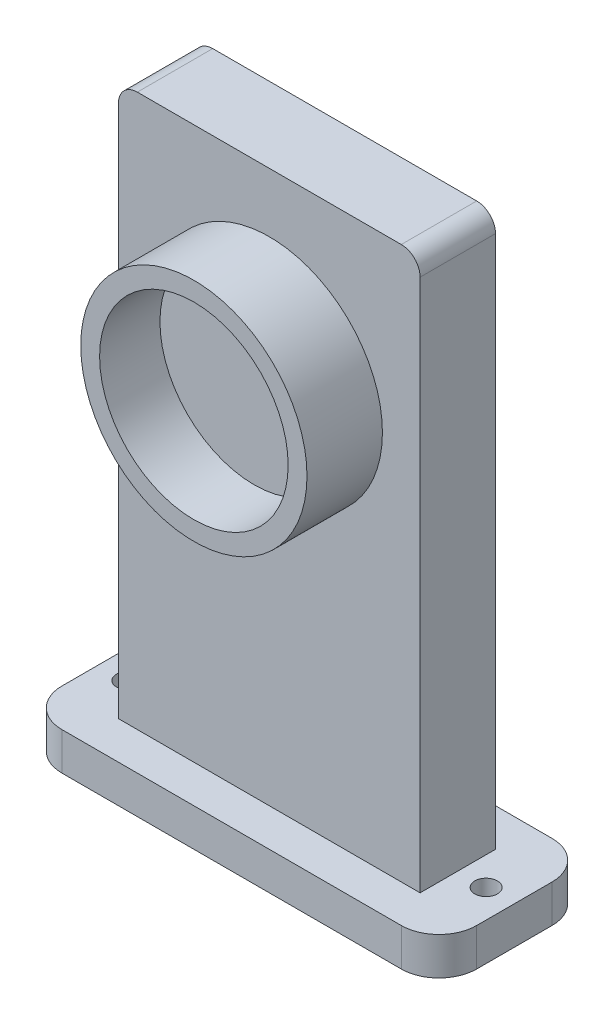
SolidWorks part; units mm, degrees
ref_plane "Front Plane" through (0, 0, 0) normal (0, 0, 1) x (1, 0, 0)
ref_plane "Top Plane" through (0, 0, 0) normal (0, 1, 0) x (1, 0, 0)
ref_plane "Right Plane" through (0, 0, 0) normal (1, 0, 0) x (0, 0, -1)
sketch "Sketch1" plane through (0, 0, 0) normal (0, 0, 1) x (1, 0, 0)
  line L5 (-20, 55.35) -> (20, -55.35) construction
  line L6 (-20, -55.35) -> (20, 55.35) construction
  line L14 (-20, 55.35) -> (20, 55.35)
  line L15 (-20, 55.35) -> (-20, -55.35)
  line L16 (-20, -55.35) -> (20, -55.35)
  line L17 (20, 55.35) -> (20, -55.35)
  point P0 (0, 0)
  dimension "D1" = 110.7
  dimension "D2" = 40
extrude "Boss-Extrude1" add sketch "Sketch1" along normal blind 10
sketch "Sketch4" plane through (0, 0, 10) normal (0, 0, 1) x (1, 0, 0)
  circle A0 centre (0, 0) radius 15
  dimension "D1" = 30
extrude "Boss-Extrude3" add sketch "Sketch4" along normal blind 10
sketch "Sketch5" plane through (0, 0, 20) normal (0, 0, 1) x (1, 0, 0)
  circle A0 centre (0, 0) radius 12.5
  dimension "D1" = 25
extrude "Cut-Extrude2" cut sketch "Sketch5" against normal blind 8
sketch "Sketch6" plane through (0, 55.35, 0) normal (0, 1, 0) x (1, 0, 0)
  line L1 (-20, 0) -> (20, 0)
  line L2 (-20, 0) -> (-20, -10)
  line L3 (-20, -10) -> (20, -10)
  line L4 (20, 0) -> (20, -10)
extrude "Cut-Extrude3" cut sketch "Sketch6" against normal blind 32.5
fillet "Fillet4" radius 2.5 2 edges at (20, 22.85, 5) (-20, 22.85, 5)
sketch "Sketch11" plane through (0, -55.35, 0) normal (0, -1, 0) x (1, 0, 0)
  line L0 (0, 10) -> (0, 0) construction
  line L1 (-20, 10) -> (20, 10) construction
  line L2 (-27.5, 5) -> (-20, 5) construction
  line L3 (-22.5, 15) -> (22.5, 15)
  line L4 (-27.5, 10) -> (-27.5, 0)
  line L5 (-22.5, -5) -> (22.5, -5)
  line L6 (27.5, 10) -> (27.5, 0)
  line L7 (-27.5, 15) -> (27.5, -5) construction
  line L8 (-27.5, -5) -> (27.5, 15) construction
  line L9 (-20, 10) -> (-20, 0) construction
  line L11 (-20, 10) -> (20, 10)
  line L12 (-20, 10) -> (-20, 0)
  line L13 (-20, 0) -> (20, 0)
  line L14 (20, 10) -> (20, 0)
  line L15 (-20, 10) -> (20, 0) construction
  line L16 (-20, 0) -> (20, 10) construction
  arc A0 (22.5, 15) -> (27.5, 10) centre (22.5, 10) cw
  arc A1 (22.5, -5) -> (27.5, 0) centre (22.5, 0) ccw
  arc A2 (-27.5, 0) -> (-22.5, -5) centre (-22.5, 0) ccw
  arc A3 (-22.5, 15) -> (-27.5, 10) centre (-22.5, 10) ccw
  circle A4 centre (-23.75, 5) radius 1.5
  circle A5 centre (23.75, 5) radius 1.5
  point P5 (0, 5)
  point P30 (0, 5)
  dimension "D3" = 5
  dimension "D4" = 3
  dimension "D1" = 20
  dimension "D2" = 55
extrude "Boss-Extrude4" add sketch "Sketch11" against normal blind 5
